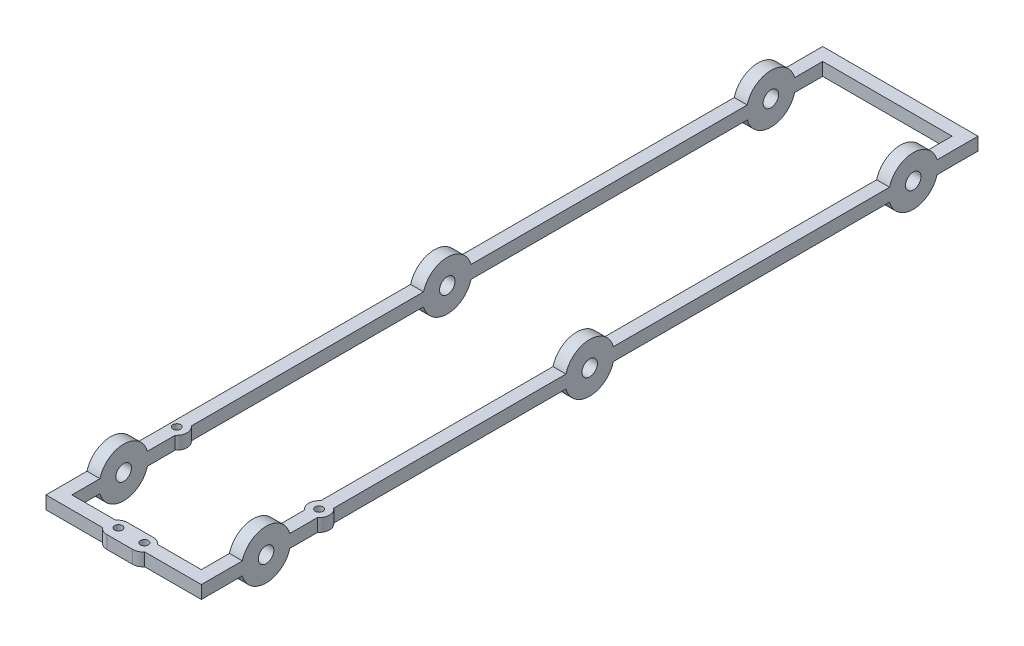
SolidWorks part; units mm, degrees
ref_plane "Front Plane" through (0, 0, 0) normal (0, 0, 1) x (1, 0, 0)
ref_plane "Top Plane" through (0, 0, 0) normal (0, 1, 0) x (1, 0, 0)
ref_plane "Right Plane" through (0, 0, 0) normal (1, 0, 0) x (0, 0, -1)
sketch "Sketch2" plane through (0, 0, 0) normal (1, 0, 0) x (0, 0, -1)
  line L0 (159.1652, 5) -> (265.8348, 5)
  line L1 (0, 0) -> (15.8348, 0)
  line L2 (0, 0) -> (0, 5)
  line L3 (0, 5) -> (15.8348, 5)
  line L4 (300, 0) -> (300, 5)
  line L5 (159.1652, 0) -> (265.8348, 0)
  line L6 (284.1652, 5) -> (300, 5)
  line L7 (284.1652, 0) -> (300, 0)
  line L8 (34.1652, 5) -> (140.8348, 5)
  line L9 (34.1652, 0) -> (140.8348, 0)
  arc A0 (159.1652, 5) -> (140.8348, 5) centre (150, 2.5) ccw
  circle A1 centre (150, 2.5) radius 3
  arc A2 (140.8348, 0) -> (159.1652, 0) centre (150, 2.5) ccw
  arc A3 (265.8348, 0) -> (284.1652, 0) centre (275, 2.5) ccw
  circle A4 centre (275, 2.5) radius 3
  arc A5 (284.1652, 5) -> (265.8348, 5) centre (275, 2.5) ccw
  arc A6 (34.1652, 5) -> (15.8348, 5) centre (25, 2.5) ccw
  circle A7 centre (25, 2.5) radius 3
  arc A8 (15.8348, 0) -> (34.1652, 0) centre (25, 2.5) ccw
  dimension "D3" = 19
  dimension "D4" = 6
  dimension "D6" = 19
  dimension "D7" = 6
  dimension "D8" = 19
  dimension "D9" = 6
  dimension "D1" = 300
  dimension "D2" = 5
  dimension "D5" = 25
  dimension "D10" = 25
extrude "Boss-Extrude1" add sketch "Sketch2" along normal blind 180
sketch "Sketch3" plane through (0, 5, 0) normal (0, 1, 0) x (1, 0, 0)
  line L0 (180, 300) -> (0, 300) construction
  line L1 (175, 295) -> (125, 295)
  line L2 (175, 295) -> (175, 5)
  line L3 (175, 5) -> (125, 5)
  line L4 (125, 295) -> (125, 5)
  line L5 (180, 159.1652) -> (180, 265.8348) construction
  line L6 (180, 0) -> (0, 0) construction
  line L7 (115, 295) -> (115, 5)
  line L8 (115, 295) -> (65, 295)
  line L9 (65, 295) -> (65, 5)
  line L10 (115, 5) -> (65, 5)
  line L11 (55, 295) -> (55, 5)
  line L12 (55, 295) -> (5, 295)
  line L13 (5, 295) -> (5, 5)
  line L14 (55, 5) -> (5, 5)
  dimension "D1" = 5
  dimension "D2" = 5
  dimension "D3" = 5
  dimension "D4" = 50
  dimension "D5" = 3
extrude "Cut-Extrude1" cut sketch "Sketch3" against normal through all both and the other way through all
sketch "Sketch5" plane through (0, 5, 0) normal (0, 1, 0) x (1, 0, 0)
  line L0 (55, 140.8348) -> (55, 34.1652) construction
  line L1 (60, -64.8144) -> (219.1227, -64.8144)
  line L2 (60, -64.8144) -> (60, 344.6851)
  line L3 (60, 344.6851) -> (219.1227, 344.6851)
  line L4 (219.1227, -64.8144) -> (219.1227, 344.6851)
  dimension "D1" = 5
extrude "Cut-Extrude2" cut sketch "Sketch5" against normal through all both and the other way through all
sketch "Sketch8" plane through (0, 0, 0) normal (0, -1, 0) x (-1, 0, 0)
  line L0 (-60, 0) -> (0, 0) construction
  line L2 (-60, 140.8348) -> (-60, 34.1652) construction
  line L3 (-25, 2.5) -> (-35, 2.5) construction
  line L4 (-25, -1.5) -> (-35, -1.5)
  line L5 (-25, 6.5) -> (-35, 6.5)
  line L6 (-55, 5) -> (-55, 15.8348) construction
  line L7 (-2.4756, 44) -> (-2.4756, 52)
  circle A1 centre (-57.5, 48) radius 4
  arc A4 (-25, -1.5) -> (-25, 6.5) centre (-25, 2.5) ccw
  arc A5 (-35, 6.5) -> (-35, -1.5) centre (-35, 2.5) ccw
  arc A6 (-2.4756, 44) -> (-2.4756, 52) centre (-2.4756, 48) cw
  point P12 (-30, 2.5)
  dimension "D3" = 8
  dimension "D4" = 4
  dimension "D9" = 4
  dimension "D2" = 48
  dimension "D5" = 48
  dimension "D6" = 2.5
  dimension "D7" = 2.5
  dimension "D8" = 10
  dimension "D10" = 20
extrude "Boss-Extrude3" add sketch "Sketch8" against normal blind 5
sketch "Sketch9" plane through (0, 0, 0) normal (0, -1, 0) x (-1, 0, 0)
  line L0 (-21.8775, 0) -> (0, 0) construction
  line L1 (-60, 0) -> (-38.1225, 0) construction
  line L3 (-55, 5) -> (-55, 15.8348) construction
  line L4 (-60, 44.8775) -> (-60, 34.1652) construction
  line L6 (-5, 44.8972) -> (-5, 34.1652) construction
  circle A0 centre (-25, 3) radius 1.5
  circle A1 centre (-35, 3) radius 1.5
  circle A3 centre (-57.5, 48) radius 1.5
  circle A5 centre (-2.5, 48) radius 1.5
  dimension "D3" = 3
  dimension "D4" = 3
  dimension "D8" = 3
  dimension "D11" = 2.5
  dimension "D10" = 3
  dimension "D1" = 3
  dimension "D2" = 3
  dimension "D5" = 10
  dimension "D6" = 20
  dimension "D7" = 48
  dimension "D9" = 2.5
extrude "Cut-Extrude4" cut sketch "Sketch9" against normal blind 5
